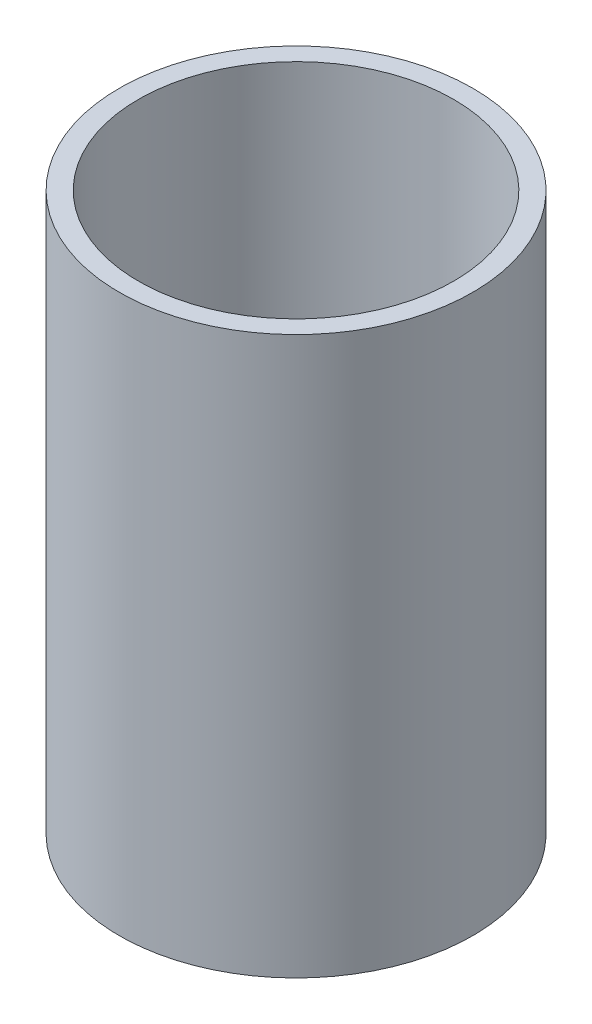
SolidWorks part; units mm, degrees
material "Alloy Steel"
ref_plane "Front Plane" through (0, 0, 0) normal (0, 0, 1) x (1, 0, 0)
ref_plane "Top Plane" through (0, 0, 0) normal (0, 1, 0) x (1, 0, 0)
ref_plane "Right Plane" through (0, 0, 0) normal (1, 0, 0) x (0, 0, -1)
sketch "BaseS" plane through (0, 0, 0) normal (0, 1, 0) x (1, 0, 0)
  circle A0 centre (0, 0) radius 4.1
  circle A1 centre (0, 0) radius 4.6
  dimension "InnerDia" = 8.2
  dimension "RefOuterDia" = 9.2
  dimension "Thickness" = 0.5
extrude "BASE" add sketch "BaseS" along normal mid plane 14.5
